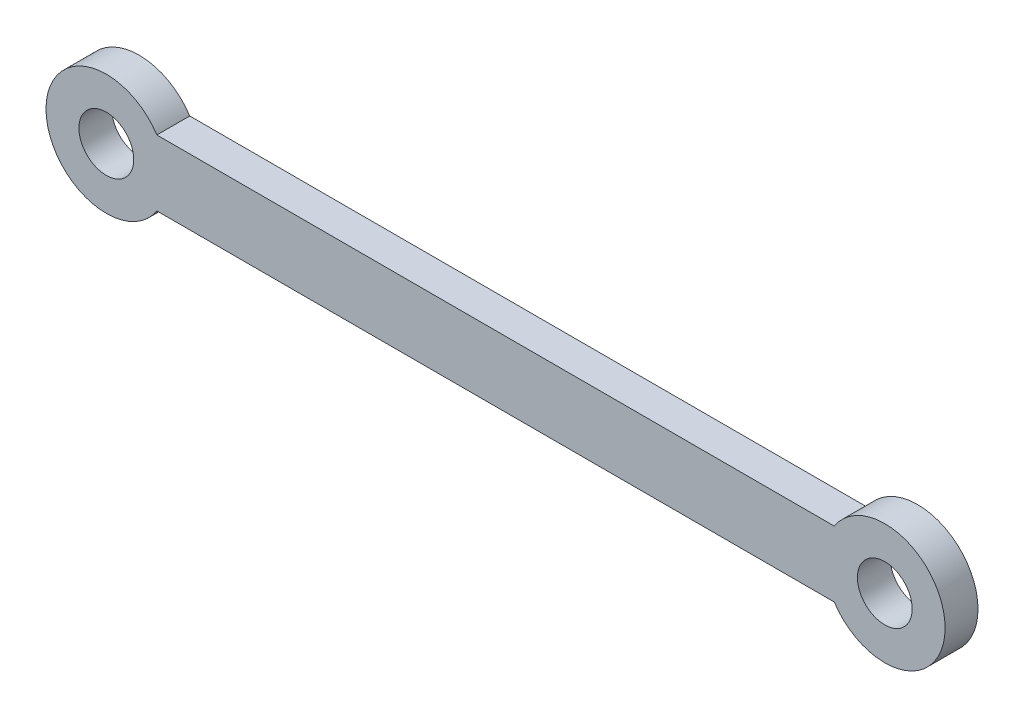
SolidWorks part; units mm, degrees
ref_plane "前视基准面" through (0, 0, 0) normal (0, 0, 1) x (1, 0, 0)
ref_plane "上视基准面" through (0, 0, 0) normal (0, 1, 0) x (1, 0, 0)
ref_plane "右视基准面" through (0, 0, 0) normal (1, 0, 0) x (0, 0, -1)
sketch "草图1" plane through (0, 0, 0) normal (0, 0, 1) x (1, 0, 0)
  line L0 (1.65, 0) -> (-1.65, 0) construction
  line L1 (0, 0) -> (71, 0) construction
  line L4 (4.6098, 3) -> (66.3902, 3)
  line L6 (4.6098, -3) -> (66.3902, -3)
  circle A0 centre (0, 0) radius 2.5
  circle A1 centre (71, 0) radius 2.5
  circle A2 centre (0, 0) radius 5.5
  circle A3 centre (71, 0) radius 5.5
  dimension "D1" = 5
  dimension "D2" = 5
  dimension "D3" = 71
  dimension "D5" = 3
  dimension "D6" = 3
  dimension "D4" = 3
extrude "凸台-拉伸1" add sketch "草图1" along normal blind 3
